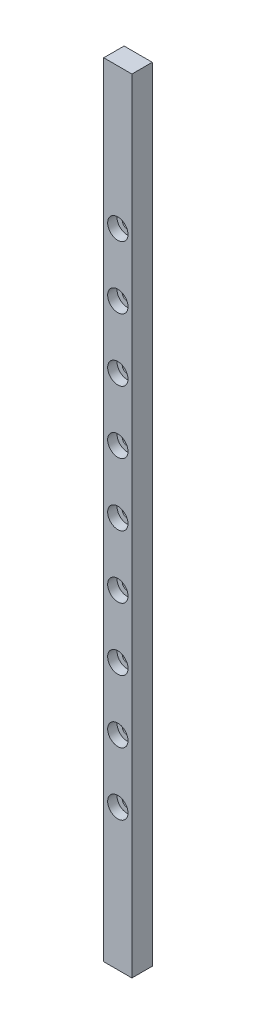
SolidWorks part; units mm, degrees
material "合金钢"
ref_plane "前视基准面" through (0, 0, 0) normal (0, 0, 1) x (1, 0, 0)
ref_plane "上视基准面" through (0, 0, 0) normal (0, 1, 0) x (1, 0, 0)
ref_plane "右视基准面" through (0, 0, 0) normal (1, 0, 0) x (0, 0, -1)
sketch "草图1" plane through (0, 0, 0) normal (0, 0, 1) x (1, 0, 0)
  line L1 (-4.5, 125) -> (4.5, 125)
  line L2 (-4.5, 125) -> (-4.5, -125)
  line L3 (-4.5, -125) -> (4.5, -125)
  line L4 (4.5, 125) -> (4.5, -125)
  line L5 (-4.5, 125) -> (4.5, -125) construction
  line L6 (-4.5, -125) -> (4.5, 125) construction
  point P0 (0, 0)
  dimension "D1" = 9
  dimension "D2" = 250
extrude "凸台-拉伸1" add sketch "草图1" along normal blind 6.5
ref_plane "基准面1" through (0, 0, 6.5) normal (0, 0, 1) x (1, 0, 0)
sketch "草图2" plane through (0, 0, 6.5) normal (0, 0, 1) x (1, 0, 0)
  circle A0 centre (0, 0) radius 1.6
  circle A1 centre (0, 20) radius 1.6
  circle A2 centre (0, 40) radius 1.6
  circle A3 centre (0, 60) radius 1.6
  circle A4 centre (0, 80) radius 1.6
  circle A5 centre (0, -20) radius 1.6
  circle A6 centre (0, -40) radius 1.6
  circle A7 centre (0, -60) radius 1.6
  circle A8 centre (0, -80) radius 1.6
  dimension "D1" = 3.2
  dimension "D2" = 5
  dimension "D3" = 5
extrude "切除-拉伸1" cut sketch "草图2" against normal through all
sketch "草图3" plane through (0, 0, 6.5) normal (0, 0, 1) x (1, 0, 0)
  circle A0 centre (0, 80) radius 3.25
  circle A1 centre (0, 60) radius 3.25
  circle A2 centre (0, 40) radius 3.25
  circle A3 centre (0, 20) radius 3.25
  circle A4 centre (0, 0) radius 3.25
  circle A5 centre (0, -20) radius 3.25
  circle A6 centre (0, -40) radius 3.25
  circle A7 centre (0, -60) radius 3.25
  circle A8 centre (0, -80) radius 3.25
  dimension "D1" = 6.5
  dimension "D2" = 9
extrude "切除-拉伸2" cut sketch "草图3" against normal blind 3
